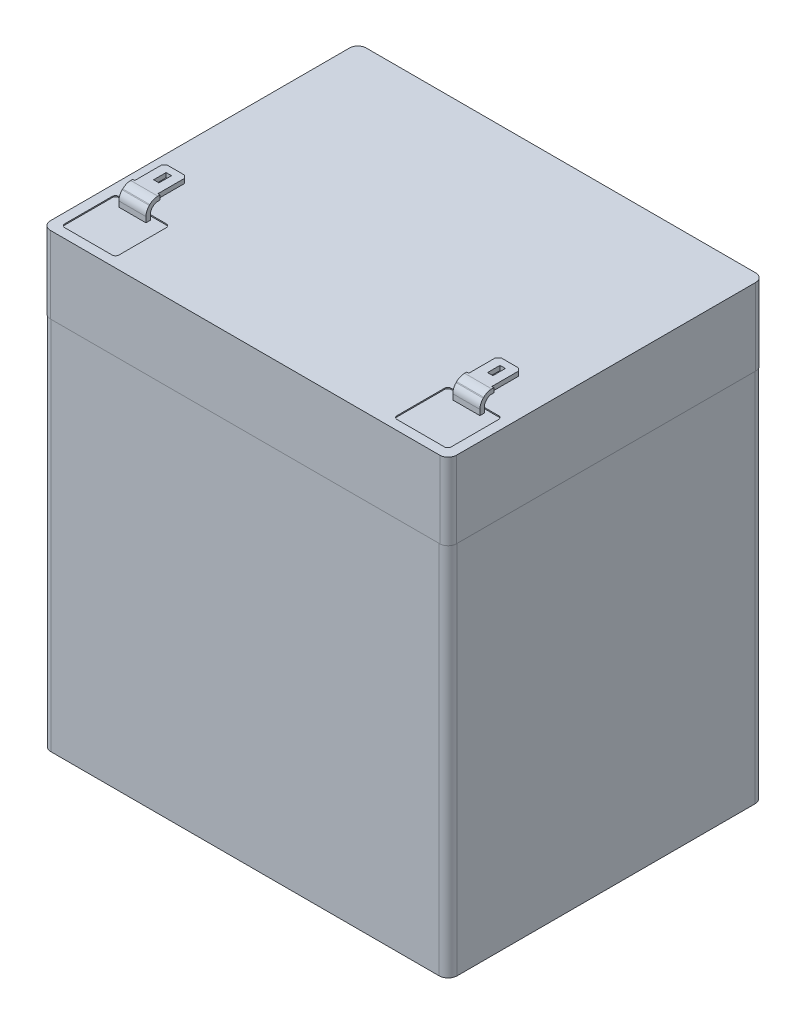
SolidWorks part; units mm, degrees
ref_plane "Front Plane" through (0, 0, 0) normal (0, 0, 1) x (1, 0, 0)
ref_plane "Top Plane" through (0, 0, 0) normal (0, 1, 0) x (1, 0, 0)
ref_plane "Right Plane" through (0, 0, 0) normal (1, 0, 0) x (0, 0, -1)
sketch "Sketch1" plane through (0, 0, 0) normal (0, 1, 0) x (1, 0, 0)
  line L1 (-43, 35) -> (43, 35)
  line L2 (-45, 33) -> (-45, -33)
  line L3 (-43, -35) -> (43, -35)
  line L4 (45, 33) -> (45, -33)
  line L5 (-45, 35) -> (45, -35) construction
  line L6 (-45, -35) -> (45, 35) construction
  arc A0 (43, -35) -> (45, -33) centre (43, -33) ccw
  arc A1 (45, 33) -> (43, 35) centre (43, 33) ccw
  arc A2 (-43, 35) -> (-45, 33) centre (-43, 33) ccw
  arc A3 (-43, -35) -> (-45, -33) centre (-43, -33) cw
  point P0 (0, 0)
  dimension "D1" = 2
extrude "Boss-Extrude1" add sketch "Sketch1" along normal blind 83
sketch "Sketch2" plane through (0, 83, 0) normal (0, 1, 0) x (1, 0, 0)
  line L1 (-43.15, 35) -> (43.15, 35)
  line L2 (-45, 33.15) -> (-45, -33.15)
  line L3 (-43.15, -35) -> (43.15, -35)
  line L4 (45, 33.15) -> (45, -33.15)
  line L5 (-45, 35) -> (45, -35) construction
  line L6 (-45, -35) -> (45, 35) construction
  arc A0 (43.15, 35) -> (45, 33.15) centre (43.15, 33.15) cw
  arc A1 (45, -33.15) -> (43.15, -35) centre (43.15, -33.15) cw
  arc A2 (-43.15, -35) -> (-45, -33.15) centre (-43.15, -33.15) cw
  arc A3 (-43.15, 35) -> (-45, 33.15) centre (-43.15, 33.15) ccw
  point P0 (0, 0)
  dimension "D1" = 1.85
extrude "Boss-Extrude2" add sketch "Sketch2" along normal blind 17 separate body
sketch "Sketch3" plane through (0, 100, 0) normal (0, 1, 0) x (1, 0, 0)
  line L0 (0, 35) -> (0, 25.3232) construction
  line L1 (-42.0683, -20.8904) -> (-31.5683, -20.8904)
  line L2 (-42.8183, -21.6404) -> (-42.8183, -32.1404)
  line L3 (-42.0683, -32.8904) -> (-31.5683, -32.8904)
  line L4 (-30.8183, -21.6404) -> (-30.8183, -32.1404)
  line L6 (30.8183, -21.6404) -> (30.8183, -32.1404)
  line L7 (42.0683, -32.8904) -> (31.5683, -32.8904)
  line L8 (42.8183, -21.6404) -> (42.8183, -32.1404)
  line L9 (42.0683, -20.8904) -> (31.5683, -20.8904)
  arc A0 (30.8183, -32.1404) -> (31.5683, -32.8904) centre (31.5683, -32.1404) ccw
  arc A1 (42.0683, -32.8904) -> (42.8183, -32.1404) centre (42.0683, -32.1404) ccw
  arc A2 (42.8183, -21.6404) -> (42.0683, -20.8904) centre (42.0683, -21.6404) ccw
  arc A3 (31.5683, -20.8904) -> (30.8183, -21.6404) centre (31.5683, -21.6404) ccw
  arc A4 (-42.8183, -32.1404) -> (-42.0683, -32.8904) centre (-42.0683, -32.1404) ccw
  arc A5 (-31.5683, -32.8904) -> (-30.8183, -32.1404) centre (-31.5683, -32.1404) ccw
  arc A6 (-30.8183, -21.6404) -> (-31.5683, -20.8904) centre (-31.5683, -21.6404) ccw
  arc A7 (-42.0683, -20.8904) -> (-42.8183, -21.6404) centre (-42.0683, -21.6404) ccw
  point P13 (30.8183, -32.8904)
  point P16 (42.8183, -32.8904)
  point P19 (42.8183, -20.8904)
  point P22 (30.8183, -20.8904)
  point P25 (-42.8183, -32.8904)
  point P28 (-30.8183, -32.8904)
  point P31 (-30.8183, -20.8904)
  point P34 (-42.8183, -20.8904)
  dimension "D1" = 0.75
extrude "Cut-Extrude1" cut sketch "Sketch3" against normal blind 0.5
sketch "Sketch5" plane through (0, 99.5, 0) normal (0, 1, 0) x (1, 0, 0)
  line L0 (0, 35) -> (0, 25.3232) construction
  line L1 (-42.0683, -20.8904) -> (-31.5683, -20.8904)
  line L2 (-42.8183, -21.6404) -> (-42.8183, -32.1404)
  line L3 (-42.0683, -32.8904) -> (-31.5683, -32.8904)
  line L4 (-30.8183, -21.6404) -> (-30.8183, -32.1404)
  line L6 (30.8183, -21.6404) -> (30.8183, -32.1404)
  line L7 (42.0683, -32.8904) -> (31.5683, -32.8904)
  line L8 (42.8183, -21.6404) -> (42.8183, -32.1404)
  line L9 (42.0683, -20.8904) -> (31.5683, -20.8904)
  arc A0 (30.8183, -32.1404) -> (31.5683, -32.8904) centre (31.5683, -32.1404) ccw
  arc A1 (42.0683, -32.8904) -> (42.8183, -32.1404) centre (42.0683, -32.1404) ccw
  arc A2 (42.8183, -21.6404) -> (42.0683, -20.8904) centre (42.0683, -21.6404) ccw
  arc A3 (31.5683, -20.8904) -> (30.8183, -21.6404) centre (31.5683, -21.6404) ccw
  arc A4 (-42.8183, -32.1404) -> (-42.0683, -32.8904) centre (-42.0683, -32.1404) ccw
  arc A5 (-31.5683, -32.8904) -> (-30.8183, -32.1404) centre (-31.5683, -32.1404) ccw
  arc A6 (-30.8183, -21.6404) -> (-31.5683, -20.8904) centre (-31.5683, -21.6404) ccw
  arc A7 (-42.0683, -20.8904) -> (-42.8183, -21.6404) centre (-42.0683, -21.6404) ccw
  point P13 (30.8183, -32.8904)
  point P16 (42.8183, -32.8904)
  point P19 (42.8183, -20.8904)
  point P22 (30.8183, -20.8904)
  point P25 (-42.8183, -32.8904)
  point P28 (-30.8183, -32.8904)
  point P31 (-30.8183, -20.8904)
  point P34 (-42.8183, -20.8904)
  dimension "D1" = 0.75
extrude "Boss-Extrude3" add sketch "Sketch5" along normal blind 0.25
ref_plane "Plane1" through (-37, 0, 0) normal (-1, 0, 0) x (0, 0, 1)
sketch "Sketch6" plane through (-37, 0, 0) normal (-1, 0, 0) x (0, 0, 1)
  line L0 (20.9649, 99.1668) -> (20.9649, 105.2382) construction
  line L1 (21.9636, 100) -> (21.9636, 101.1997)
  line L2 (-33.15, 100) -> (33.15, 100) construction
  line L3 (21.5242, 102.2604) -> (21.4043, 102.3803)
  line L4 (20.3436, 102.8197) -> (13.3436, 102.8197)
  arc A0 (21.9636, 101.1997) -> (21.5242, 102.2604) centre (20.4636, 101.1997) ccw
  arc A1 (21.4043, 102.3803) -> (20.3436, 102.8197) centre (20.3436, 101.3197) ccw
  point P12 (20.9649, 102.8197)
  dimension "D1" = 1.5
extrude "Extrude-Thin1" add sketch "Sketch6" along normal mid plane 6 separate body thin
ref_plane "Plane2" through (34, 0, 0) normal (1, 0, 0) x (0, 0, -1)
sketch "Sketch9" plane through (34, 0, 0) normal (1, 0, 0) x (0, 0, -1)
  line L0 (0, 100) -> (0, 116.1676) construction
  line L6 (-20.3436, 102.8197) -> (-13.3436, 102.8197)
  line L7 (-21.5242, 102.2604) -> (-21.4043, 102.3803)
  line L8 (-21.9636, 100) -> (-21.9636, 101.1997)
  arc A2 (-21.4043, 102.3803) -> (-20.3436, 102.8197) centre (-20.3436, 101.3197) cw
  arc A3 (-21.9636, 101.1997) -> (-21.5242, 102.2604) centre (-20.4636, 101.1997) cw
extrude "Extrude-Thin2" add sketch "Sketch9" along normal blind 6 thin thin type one direction reverse wall 1
sketch "Sketch10" plane through (0, 103.8197, 0) normal (0, 1, 0) x (1, 0, 0)
  line L0 (-37, -13.3436) -> (-37, -5.7985) construction
  line L2 (-38.927, -13.3436) -> (-39.5495, -13.9661)
  line L3 (-40, -13.3436) -> (-34, -13.3436) construction
  line L4 (-39.5495, -13.9661) -> (-39.5495, -19.8735)
  line L5 (-39.5495, -19.8735) -> (-40, -19.8735)
  line L6 (-40, -20.3436) -> (-40, -13.3436) construction
  line L7 (-40, -19.8735) -> (-40, -13.3436)
  line L8 (-40, -13.3436) -> (-38.927, -13.3436)
  line L9 (-34, -13.3436) -> (-35.073, -13.3436)
  line L10 (-34, -19.8735) -> (-34, -13.3436)
  line L11 (-34.4505, -19.8735) -> (-34, -19.8735)
  line L12 (-34.4505, -13.9661) -> (-34.4505, -19.8735)
  line L13 (-35.073, -13.3436) -> (-34.4505, -13.9661)
  line L14 (0, 35) -> (0, -51.7565) construction
  line L15 (-37.6, -14.9006) -> (-36.4, -14.9006)
  line L16 (-37.6, -14.9006) -> (-37.6, -17.6758)
  line L17 (-37.6, -17.6758) -> (-36.4, -17.6758)
  line L18 (-36.4, -14.9006) -> (-36.4, -17.6758)
  line L19 (-37.6, -14.9006) -> (-36.4, -17.6758) construction
  line L20 (-37.6, -17.6758) -> (-36.4, -14.9006) construction
  line L22 (37.6, -17.6758) -> (36.4, -14.9006) construction
  line L23 (37.6, -14.9006) -> (36.4, -17.6758) construction
  line L24 (36.4, -14.9006) -> (36.4, -17.6758)
  line L25 (37.6, -17.6758) -> (36.4, -17.6758)
  line L26 (37.6, -14.9006) -> (37.6, -17.6758)
  line L27 (37.6, -14.9006) -> (36.4, -14.9006)
  line L28 (35.073, -13.3436) -> (34.4505, -13.9661)
  line L29 (34.4505, -13.9661) -> (34.4505, -19.8735)
  line L30 (34.4505, -19.8735) -> (34, -19.8735)
  line L31 (34, -19.8735) -> (34, -13.3436)
  line L32 (34, -13.3436) -> (35.073, -13.3436)
  line L33 (40, -13.3436) -> (38.927, -13.3436)
  line L34 (40, -19.8735) -> (40, -13.3436)
  line L35 (39.5495, -19.8735) -> (40, -19.8735)
  line L36 (39.5495, -13.9661) -> (39.5495, -19.8735)
  line L37 (38.927, -13.3436) -> (39.5495, -13.9661)
  point P17 (-37, -16.2882)
  point P39 (37, -16.2882)
extrude "Cut-Extrude2" cut sketch "Sketch10" against normal blind 1
